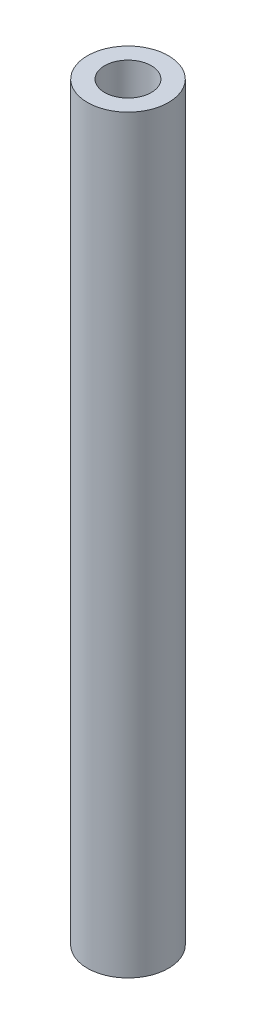
SolidWorks part; units mm, degrees
ref_plane "Front Plane" through (0, 0, 0) normal (0, 0, 1) x (1, 0, 0)
ref_plane "Top Plane" through (0, 0, 0) normal (0, 1, 0) x (1, 0, 0)
ref_plane "Right Plane" through (0, 0, 0) normal (1, 0, 0) x (0, 0, -1)
sketch "Sketch1" plane through (0, 0, 0) normal (0, 1, 0) x (1, 0, 0)
  circle A0 centre (0, 0) radius 2
  dimension "D1" = 4
extrude "Boss-Extrude1" add sketch "Sketch1" along normal blind 37
sketch "Sketch2" plane through (0, 0, 0) normal (0, -1, 0) x (1, 0, 0)
  circle A0 centre (0, 0) radius 1.15
  dimension "D1" = 2.3
extrude "Cut-Extrude1" cut sketch "Sketch2" against normal through all
